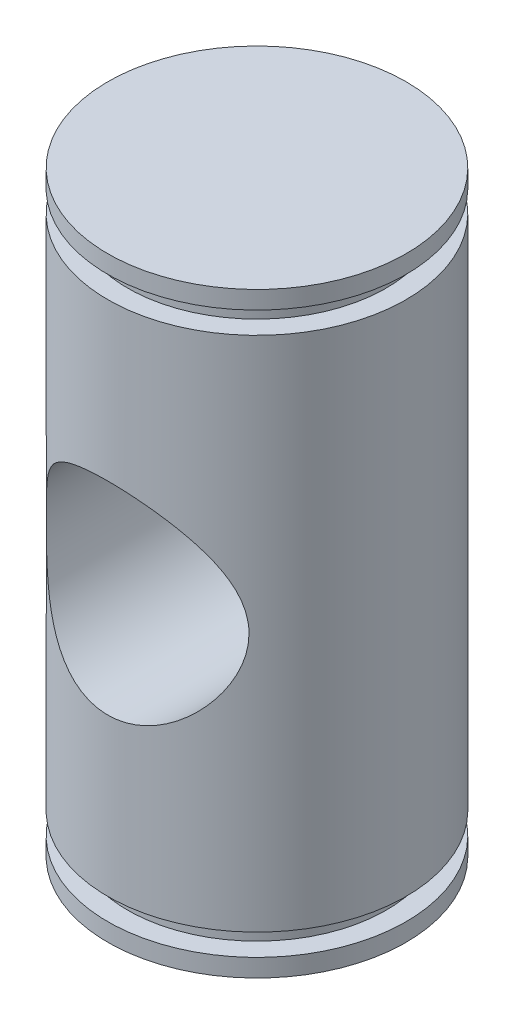
SolidWorks part; units mm, degrees
material "AISI Type A2 Tool Steel"
ref_plane "Front Plane" through (0, 0, 0) normal (0, 0, 1) x (1, 0, 0)
ref_plane "Top Plane" through (0, 0, 0) normal (0, 1, 0) x (1, 0, 0)
ref_plane "Right Plane" through (0, 0, 0) normal (1, 0, 0) x (0, 0, -1)
sketch "Sketch1" plane through (0, 0, 0) normal (0, 1, 0) x (1, 0, 0)
  circle A0 centre (0, 0) radius 7.5
  dimension "D1" = 15
extrude "Boss-Extrude1" add sketch "Sketch1" along normal blind 24
sketch "Sketch2" plane through (0, 0, 0) normal (0, 0, 1) x (1, 0, 0)
  line L0 (0, 0) -> (0, 24) construction
  line L1 (7.5, 24) -> (-7.5, 24) construction
  circle A0 centre (0, 12) radius 5.1
  dimension "D1" = 10.2
extrude "Cut-Extrude1" cut sketch "Sketch2" against normal through all both and the other way through all
sketch "Sketch3" plane through (0, 0, 0) normal (0, 0, 1) x (1, 0, 0)
  line L0 (0, 0) -> (0, 24) construction
  line L1 (-13.0227, 24) -> (6.1026, 24) construction
  line L8 (0, 24) -> (-7.5, 24)
  line L9 (-7.5, 24) -> (-7.5, 25)
  line L10 (-7.5, 25) -> (-6.5, 25)
  line L11 (-6.5, 25) -> (-6.5, 26.1)
  line L12 (-6.5, 26.1) -> (-7.5, 26.1)
  line L13 (-7.5, 26.1) -> (-7.5, 27)
  line L14 (-7.5, 27) -> (0, 27)
  line L15 (0, 27) -> (0, 24)
  line L16 (0, 12) -> (-10.1042, 12) construction
  line L17 (-7.5, -3) -> (0, -3)
  line L18 (-7.5, -2.1) -> (-7.5, -3)
  line L19 (-6.5, -2.1) -> (-7.5, -2.1)
  line L20 (-6.5, -1) -> (-6.5, -2.1)
  line L21 (-7.5, -1) -> (-6.5, -1)
  line L22 (-7.5, 0) -> (-7.5, -1)
  line L23 (0, 0) -> (-7.5, 0)
  line L24 (0, -3) -> (0, 0)
  point P5 (-7, 26.1)
  dimension "D1" = 1
  dimension "D2" = 1.1
  dimension "D3" = 6.5
  dimension "D4" = 7.5
  dimension "D5" = 3
revolve "Revolve1" add sketch "Sketch3" angle 360 about L0
